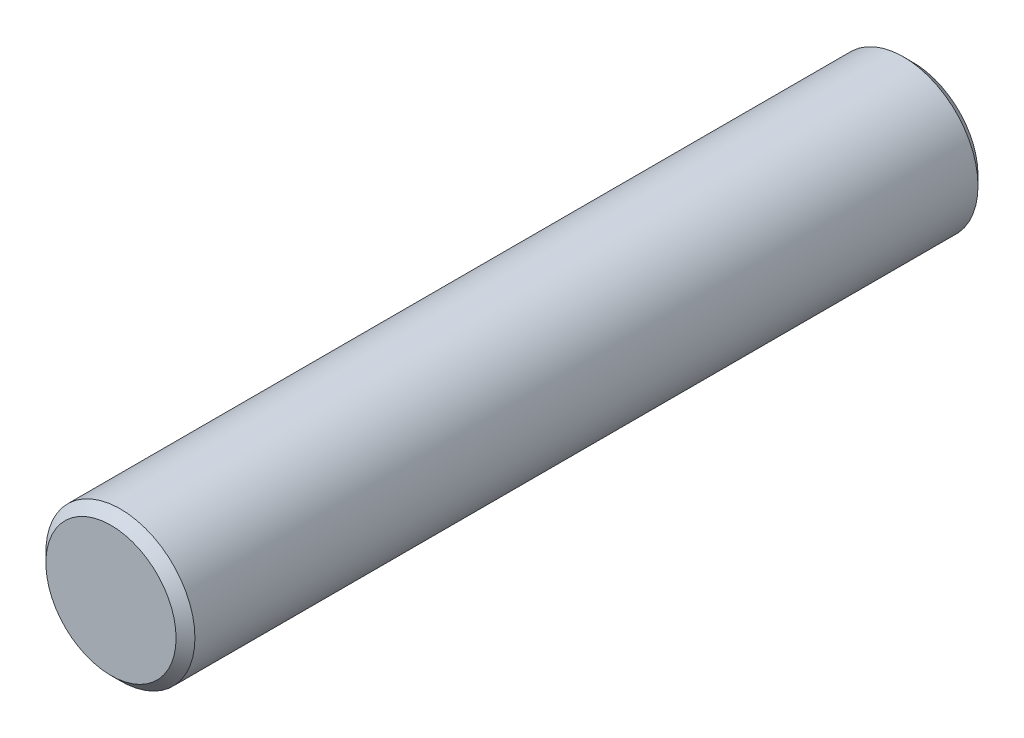
SolidWorks part; units mm, degrees
ref_plane "Plane1" through (0, 0, 0) normal (0, 0, 1) x (1, 0, 0)
ref_plane "Plane2" through (0, 0, 0) normal (0, 1, 0) x (1, 0, 0)
ref_plane "Plane3" through (0, 0, 0) normal (1, 0, 0) x (0, 0, -1)
other "Configuration Table"
sketch "Sketch1" plane through (0, 0, 0) normal (0, 0, 1) x (1, 0, 0)
  circle A0 centre (0, 0) radius 0.79
  dimension "D1" = 1.58
extrude "drive shaft pin shape" add sketch "Sketch1" along normal blind 8.5
chamfer "drive shaft pin chamfer" distance 0.1 angle 45 2 edges at (0.79, 0, 0) (0.79, 0, 8.5)
